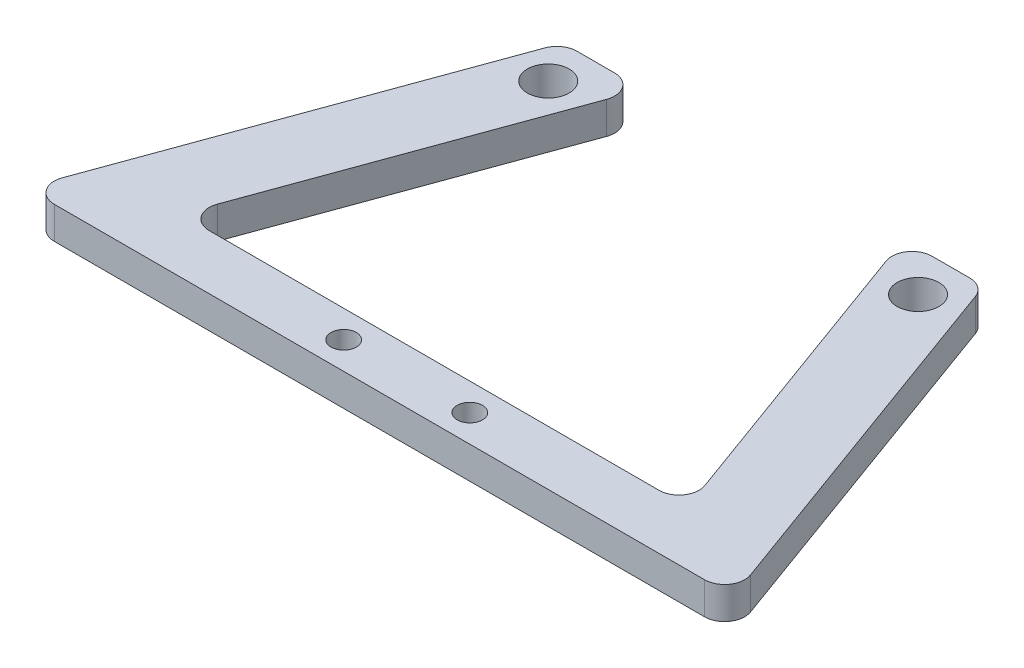
SolidWorks part; units mm, degrees
ref_plane "Front Plane" through (0, 0, 0) normal (0, 0, 1) x (1, 0, 0)
ref_plane "Top Plane" through (0, 0, 0) normal (0, 1, 0) x (1, 0, 0)
ref_plane "Right Plane" through (0, 0, 0) normal (1, 0, 0) x (0, 0, -1)
sketch "Sketch2" plane through (0, 0, 0) normal (0, 1, 0) x (1, 0, 0)
  line L0 (-0.3802, -1.0445) -> (-10.5495, -28.9845)
  line L1 (-9.0577, -31.115) -> (42.3065, -31.115)
  line L5 (34.3849, -26.797) -> (-1.1361, -26.797)
  line L6 (-2.6279, -24.6665) -> (5.5746, -2.1305)
  line L7 (4.0828, 0) -> (1.1116, 0)
  line L9 (16.6244, -26.797) -> (16.6244, -13.2922) construction
  line L11 (2.5972, -26.797) -> (2.5972, -31.115) construction
  line L12 (33.629, -1.0445) -> (43.7983, -28.9845)
  line L13 (30.6516, -26.797) -> (30.6516, -31.115) construction
  line L14 (29.6683, 0) -> (31.2294, -3.175) construction
  line L15 (29.166, 0) -> (32.1372, 0)
  line L16 (35.8767, -24.6665) -> (27.6742, -2.1305)
  line L17 (-0.7842, -2.1546) -> (4.823, -4.1954) construction
  circle A0 centre (2.0194, -3.175) radius 1.65
  circle A2 centre (11.6427, -28.956) radius 1
  circle A3 centre (21.6061, -28.956) radius 1
  circle A4 centre (31.2294, -3.175) radius 1.65
  arc A5 (43.7983, -28.9845) -> (42.3065, -31.115) centre (42.3065, -29.5275) cw
  arc A6 (35.8767, -24.6665) -> (34.3849, -26.797) centre (34.3849, -25.2095) cw
  arc A7 (-10.5495, -28.9845) -> (-9.0577, -31.115) centre (-9.0577, -29.5275) ccw
  arc A8 (-1.1361, -26.797) -> (-2.6279, -24.6665) centre (-1.1361, -25.2095) cw
  arc A9 (33.629, -1.0445) -> (32.1372, 0) centre (32.1372, -1.5875) ccw
  arc A10 (29.166, 0) -> (27.6742, -2.1305) centre (29.166, -1.5875) ccw
  arc A11 (-0.3802, -1.0445) -> (1.1116, 0) centre (1.1116, -1.5875) cw
  arc A12 (5.5746, -2.1305) -> (4.0828, 0) centre (4.0828, -1.5875) ccw
  point P2 (2.5972, -28.956)
  point P28 (44.5737, -31.115)
  point P31 (36.6521, -26.797)
  point P34 (-11.3249, -31.115)
  point P37 (-3.4033, -26.797)
  point P40 (33.2488, 0)
  point P43 (26.8988, 0)
  point P46 (0, 0)
  point P49 (6.35, 0)
  point P52 (2.0194, -3.175)
  dimension "D1" = 3.3
  dimension "D2" = 6.35
  dimension "D7" = 25.781
  dimension "D9" = 2
  dimension "D10" = 1.5875
  dimension "D3" = 3.175
  dimension "D4" = 29.21
  dimension "D5" = 110
  dimension "D6" = 4.318
  dimension "D8" = 4.9817
extrude "Boss-Extrude1" add sketch "Sketch2" along normal blind 2.54
